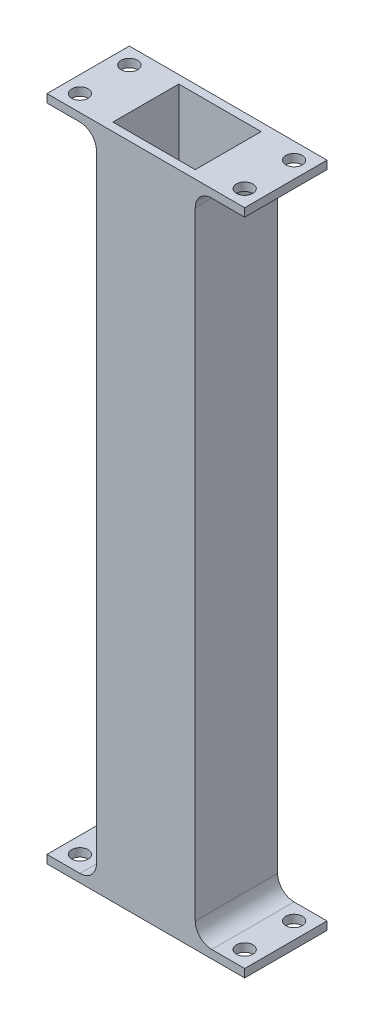
SolidWorks part; units mm, degrees
material "6061-T6 (SS)"
ref_plane "Front Plane" through (0, 0, 0) normal (1, 0, 0) x (0, 1, 0)
ref_plane "Top Plane" through (0, 0, 0) normal (0, 0, 1) x (0, 1, 0)
ref_plane "Right Plane" through (0, 0, 0) normal (0, 1, 0) x (-1, 0, 0)
sketch "Sketch1" plane through (0, 0, 0) normal (0, 1, 0) x (-1, 0, 0)
  line L1 (-30, 25) -> (30, 25)
  line L2 (-30, 25) -> (-30, -25)
  line L3 (-30, -25) -> (30, -25)
  line L4 (30, 25) -> (30, -25)
  line L5 (-30, 25) -> (30, -25) construction
  line L6 (-30, -25) -> (30, 25) construction
  point P0 (0, 0)
  dimension "D1" = 50
  dimension "D2" = 60
extrude "Boss-Extrude1" add sketch "Sketch1" along normal mid plane 400
sketch "Sketch2" plane through (0, 200, 0) normal (0, 1, 0) x (-1, 0, 0)
  line L0 (30, 25) -> (-30, 25) construction
  line L1 (-60, 25) -> (60, 25)
  line L2 (-60, 25) -> (-60, -25)
  line L3 (-60, -25) -> (60, -25)
  line L4 (60, 25) -> (60, -25)
  line L5 (-60, 25) -> (60, -25) construction
  line L6 (-60, -25) -> (60, 25) construction
  point P0 (0, 0)
  dimension "D1" = 120
extrude "Boss-Extrude2" add sketch "Sketch2" along normal mid plane 5
fillet "Fillet1" radius 10 2 edges at (-30, 197.5, 0) (30, 197.5, 0)
sketch "Sketch3" plane through (0, 197.5, 0) normal (0, -1, 0) x (1, 0, 0)
  line L0 (-1000, 0) -> (49000, 0) construction
  line L1 (50, -1003.0442) -> (50, 48996.9558) construction
  line L2 (40, 25) -> (40, -25) construction
  line L3 (60, 25) -> (60, -25) construction
  line L4 (0, -1000) -> (0, 49000) construction
  circle A0 centre (50, 15) radius 5
  circle A1 centre (50, -15) radius 5
  circle A2 centre (-50, 15) radius 5
  circle A3 centre (-50, -15) radius 5
  point P12 (0, 0)
  dimension "D1" = 10
  dimension "D2" = 15
extrude "Cut-Extrude1" cut sketch "Sketch3" against normal through all
mirror "Mirror1" about plane through (0, 0, 0) normal (0, 1, 0) of "Fillet1", "Boss-Extrude2", "Cut-Extrude1"
sketch "Sketch4" plane through (0, -202.5, 0) normal (0, -1, 0) x (1, 0, 0)
  line L0 (-25, 20) -> (-25, -20)
  line L1 (-25, -20) -> (25, -20)
  line L2 (25, -20) -> (25, 20)
  line L3 (25, 20) -> (-25, 20)
  line L4 (30, 25) -> (-30, 25)
  line L5 (-30, 25) -> (-30, -25)
  line L6 (-30, -25) -> (30, -25)
  line L7 (30, -25) -> (30, 25)
  line L8 (30, 25) -> (-30, 25) construction
  line L9 (-30, 25) -> (-30, -25) construction
  line L10 (-30, -25) -> (30, -25) construction
  line L11 (30, -25) -> (30, 25) construction
  dimension "D1" = 0
  dimension "D2" = 5
extrude "Cut-Extrude2" cut sketch "Sketch4" against normal through all
